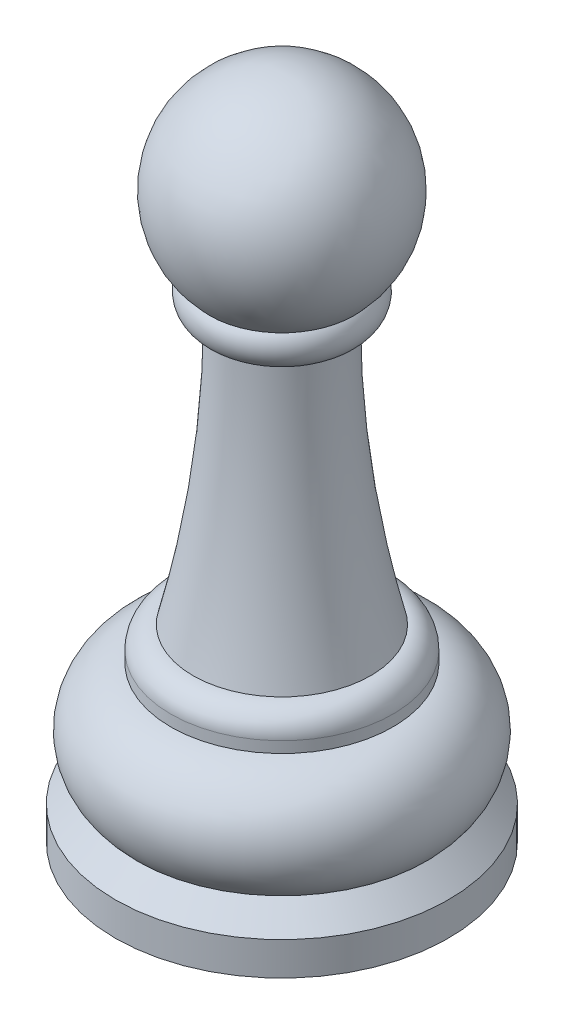
SolidWorks part; units mm, degrees
ref_plane "Alzado" through (0, 0, 0) normal (0, 0, 1) x (1, 0, 0)
ref_plane "Planta" through (0, 0, 0) normal (0, 1, 0) x (1, 0, 0)
ref_plane "Vista lateral" through (0, 0, 0) normal (1, 0, 0) x (0, 0, -1)
sketch "Croquis1" plane through (0, 0, 0) normal (0, 0, 1) x (1, 0, 0)
  line L0 (0, 0) -> (0, 60) construction
  line L1 (0, 0) -> (15, 0)
  line L2 (15, 0) -> (15, 3)
  line L3 (15, 3) -> (13, 5)
  line L6 (0, 60) -> (0, 0)
  line L7 (13, 5) -> (21.0293, 5) construction
  line L9 (10, 13.97) -> (10, 14.97)
  arc A0 (13, 5) -> (10, 13.97) centre (9.2631, 8.7369) ccw
  arc A1 (8, 16.97) -> (10, 14.97) centre (8, 14.97) cw
  arc A2 (5, 41.03) -> (8, 16.97) centre (102.9806, 41.03) ccw
  arc A3 (5, 41.03) -> (6.5, 44.29) centre (5, 43.0051) ccw
  arc A4 (6.5, 44.29) -> (0, 60) centre (0, 50.8003) ccw
  dimension "D1" = 60
  dimension "D2" = 26
  dimension "D3" = 45
  dimension "D4" = 3
  dimension "D6" = 8.97
  dimension "D7" = 20
  dimension "D8" = 1
  dimension "D9" = 16
  dimension "D11" = 10
  dimension "D12" = 24.06
  dimension "D13" = 13
  dimension "D14" = 3.26
revolve "Revolución3" add sketch "Croquis1" angle 360 about L6
